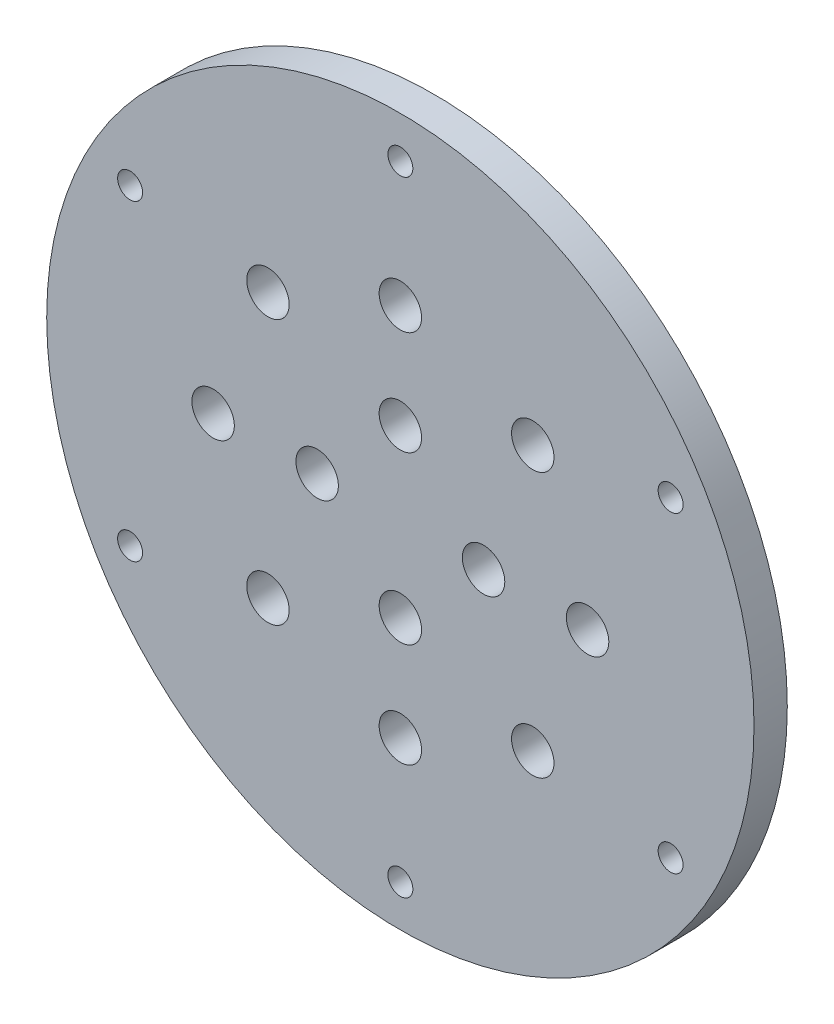
SolidWorks part; units mm, degrees
ref_plane "前视基准面" through (0, 0, 0) normal (0, 0, 1) x (1, 0, 0)
ref_plane "上视基准面" through (0, 0, 0) normal (0, 1, 0) x (1, 0, 0)
ref_plane "右视基准面" through (0, 0, 0) normal (1, 0, 0) x (0, 0, -1)
sketch "草图1" plane through (0, 0, 0) normal (0, 0, 1) x (1, 0, 0)
  circle A0 centre (0, 0) radius 85
  circle A1 centre (0, 0) radius 75 construction
  circle A2 centre (0, 75) radius 3
  circle A3 centre (64.9519, 37.5) radius 3
  circle A4 centre (64.9519, -37.5) radius 3
  circle A5 centre (0, -75) radius 3
  circle A6 centre (-64.9519, -37.5) radius 3
  circle A7 centre (-64.9519, 37.5) radius 3
  point P15 (0, 0)
  dimension "D1" = 170
  dimension "D2" = 150
  dimension "D3" = 6
  dimension "D4" = 6
extrude "凸台-拉伸1" add sketch "草图1" along normal blind 8
sketch "草图2" plane through (0, 0, 8) normal (0, 0, 1) x (1, 0, 0)
  circle A0 centre (0, 0) radius 60 construction
  circle A1 centre (0, 0) radius 45 construction
  circle A2 centre (0, 45) radius 5.1
  circle A3 centre (0, 45) radius 9 construction
  circle A4 centre (31.8198, 31.8198) radius 5.1
  circle A5 centre (31.8198, 31.8198) radius 9 construction
  circle A6 centre (45, 0) radius 5.1
  circle A7 centre (45, 0) radius 9 construction
  circle A8 centre (31.8198, -31.8198) radius 5.1
  circle A9 centre (31.8198, -31.8198) radius 9 construction
  circle A10 centre (0, -45) radius 5.1
  circle A11 centre (0, -45) radius 9 construction
  circle A12 centre (-31.8198, -31.8198) radius 5.1
  circle A13 centre (-31.8198, -31.8198) radius 9 construction
  circle A14 centre (-45, 0) radius 5.1
  circle A15 centre (-45, 0) radius 9 construction
  circle A16 centre (-31.8198, 31.8198) radius 5.1
  circle A17 centre (-31.8198, 31.8198) radius 9 construction
  circle A19 centre (0, 0) radius 20 construction
  circle A20 centre (0, 20) radius 9 construction
  circle A21 centre (0, 20) radius 5.1
  circle A22 centre (20, 0) radius 5.1
  circle A23 centre (20, 0) radius 9 construction
  circle A24 centre (0, -20) radius 5.1
  circle A25 centre (0, -20) radius 9 construction
  circle A26 centre (-20, 0) radius 5.1
  circle A27 centre (-20, 0) radius 9 construction
  point P30 (0, 0)
  point P45 (0, 0)
  dimension "D1" = 120
  dimension "D2" = 10.2
  dimension "D3" = 18
  dimension "D4" = 90
  dimension "D6" = 40
  dimension "D7" = 18
  dimension "D8" = 10.2
  dimension "D5" = 8
  dimension "D9" = 4
extrude "切除-拉伸1" cut sketch "草图2" against normal through all
